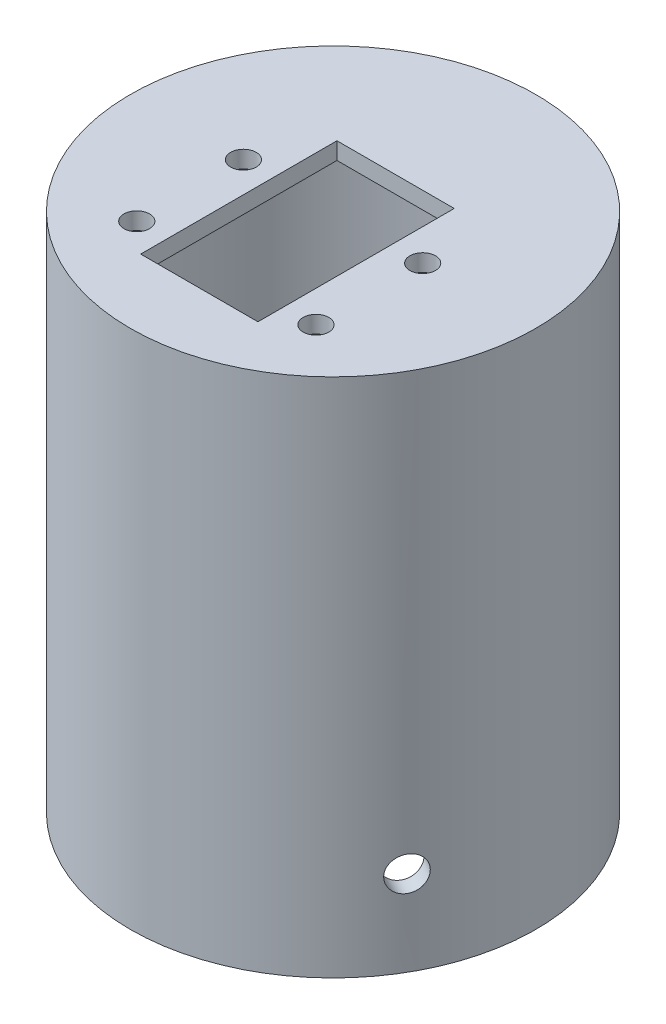
SolidWorks part; units mm, degrees
ref_plane "Front Plane" through (0, 0, 0) normal (0, 0, 1) x (1, 0, 0)
ref_plane "Top Plane" through (0, 0, 0) normal (0, 1, 0) x (1, 0, 0)
ref_plane "Right Plane" through (0, 0, 0) normal (1, 0, 0) x (0, 0, -1)
sketch "Sketch1" plane through (0, 0, 0) normal (0, 1, 0) x (1, 0, 0)
  circle A0 centre (0, 0) radius 21.75
  circle A1 centre (0, 0) radius 23.75
extrude "Boss-Extrude1" add sketch "Sketch1" along normal blind 59
sketch "Sketch2" plane through (0, 59, 0) normal (0, 1, 0) x (1, 0, 0)
  circle A0 centre (0, 0) radius 23.75
extrude "Boss-Extrude2" add sketch "Sketch2" along normal blind 2
sketch "Sketch3" plane through (0, 61, 0) normal (0, 1, 0) x (1, 0, 0)
  line L1 (0, 7.4) -> (6.8, 7.4)
  line L2 (6.8, 7.4) -> (6.8, -15.6)
  line L3 (0, 7.4) -> (-6.9427, 7.4)
  line L4 (-6.9427, 7.4) -> (-6.9427, -15.6)
  line L5 (-6.9427, -15.6) -> (6.8, -15.6)
  circle A0 centre (-10.5, 0) radius 1.5
  circle A1 centre (10.5, 0) radius 1.5
  circle A2 centre (-10.5, -12.5) radius 1.5
  circle A3 centre (10.5, -12.5) radius 1.5
extrude "Cut-Extrude1" cut sketch "Sketch3" along direction (0, 1, 0) on the side against the normal up to surface (2 mm away) contours L3 L4 L5 L2 L1 | A3 | A1 | A0 | A2
sketch "Sketch4" plane through (0, 0, 0) normal (0, 0, 1) x (1, 0, 0)
  circle A0 centre (0, 10) radius 2
extrude "Cut-Extrude2" cut sketch "Sketch4" against normal up to surface (23.6656 mm away)
pattern_circular "CirPattern1" count 3 over 360 about axis through (0, 59, 0) along (0, -1, 0) of "Cut-Extrude2"
